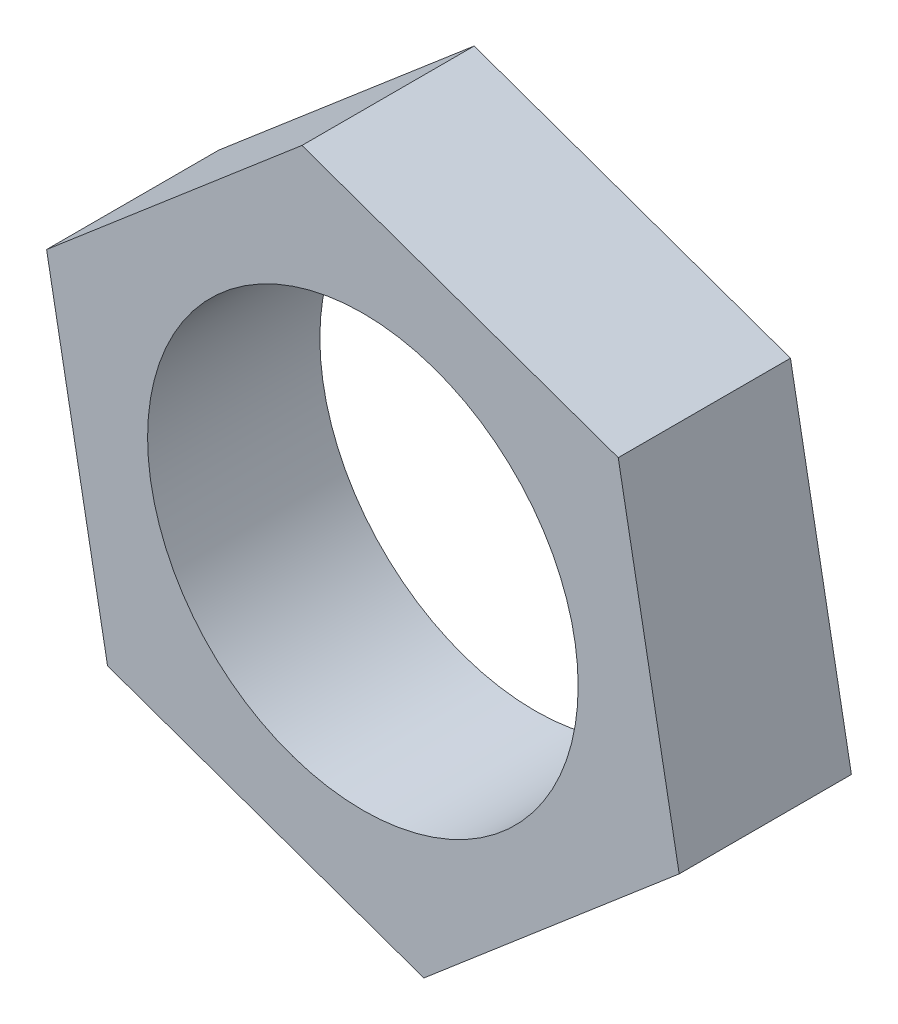
SolidWorks part; units mm, degrees
ref_plane "前视基准面" through (0, 0, 0) normal (0, 0, 1) x (1, 0, 0)
ref_plane "上视基准面" through (0, 0, 0) normal (0, 1, 0) x (1, 0, 0)
ref_plane "右视基准面" through (0, 0, 0) normal (1, 0, 0) x (0, 0, -1)
sketch "草图1" plane through (0, 0, 0) normal (0, 0, 1) x (1, 0, 0)
  line L1 (14.691, -5.2129) -> (11.86, 10.1163)
  line L2 (11.86, 10.1163) -> (-2.831, 15.3292)
  line L3 (-2.831, 15.3292) -> (-14.691, 5.2129)
  line L4 (-14.691, 5.2129) -> (-11.86, -10.1163)
  line L5 (-11.86, -10.1163) -> (2.831, -15.3292)
  line L6 (2.831, -15.3292) -> (14.691, -5.2129)
  circle A0 centre (0, 0) radius 13.5 construction
  circle A1 centre (0, 0) radius 10
  dimension "D2" = 20
  dimension "D1" = 27
extrude "拉伸1" add sketch "草图1" along normal blind 8
